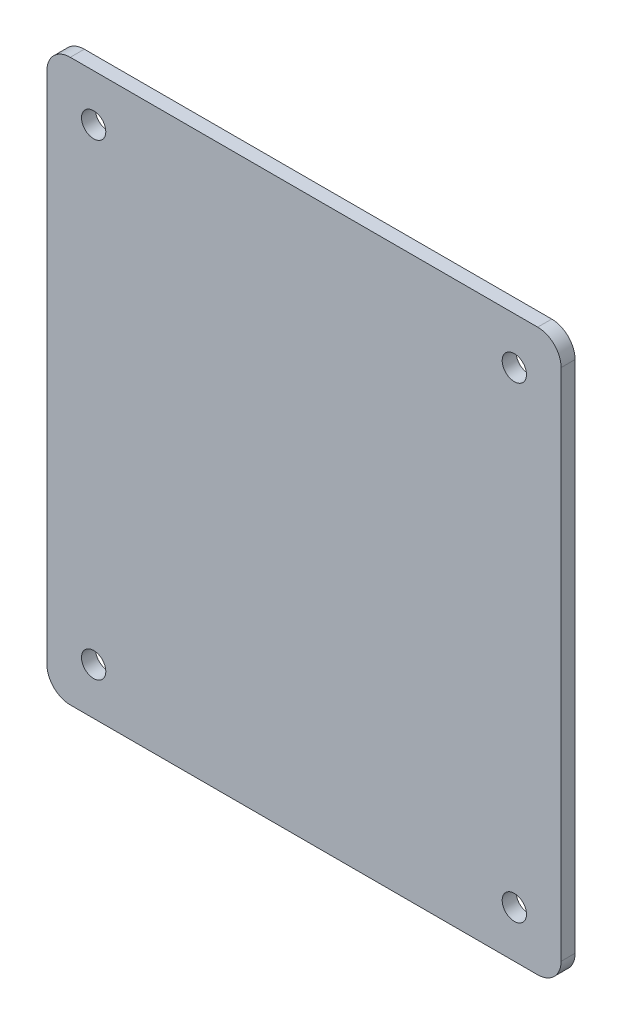
SolidWorks part; units mm, degrees
ref_plane "正面" through (0, 0, 0) normal (0, 0, 1) x (1, 0, 0)
ref_plane "平面" through (0, 0, 0) normal (0, 1, 0) x (1, 0, 0)
ref_plane "右側面" through (0, 0, 0) normal (1, 0, 0) x (0, 0, -1)
sketch "ｽｹｯﾁ2" plane through (0, 0, 0) normal (0, 0, 1) x (1, 0, 0)
  line L0 (0, -10) -> (110, -10) construction
  line L1 (0, 0) -> (110, 0)
  line L2 (0, 0) -> (0, -120)
  line L3 (0, -120) -> (110, -120)
  line L4 (110, 0) -> (110, -120)
  line L5 (0, -110) -> (110, -110) construction
  line L6 (10, -10) -> (10, -110) construction
  line L7 (100, -10) -> (100, -110) construction
  circle A0 centre (10, -10) radius 2.6
  circle A1 centre (100, -10) radius 2.6
  circle A2 centre (10, -110) radius 2.6
  circle A3 centre (100, -110) radius 2.6
  dimension "D4" = 5.2
  dimension "D5" = 10
  dimension "D6" = 10
  dimension "D7" = 100
  dimension "D1" = 10
  dimension "D2" = 110
  dimension "D8" = 10
extrude "ﾎﾞｽ - 押し出し1" add sketch "ｽｹｯﾁ2" along normal blind 3
fillet "ﾌｨﾚｯﾄ1" radius 5 4 edges at (0, -120, 1.5) (0, 0, 1.5) (110, -120, 1.5) (110, 0, 1.5)
